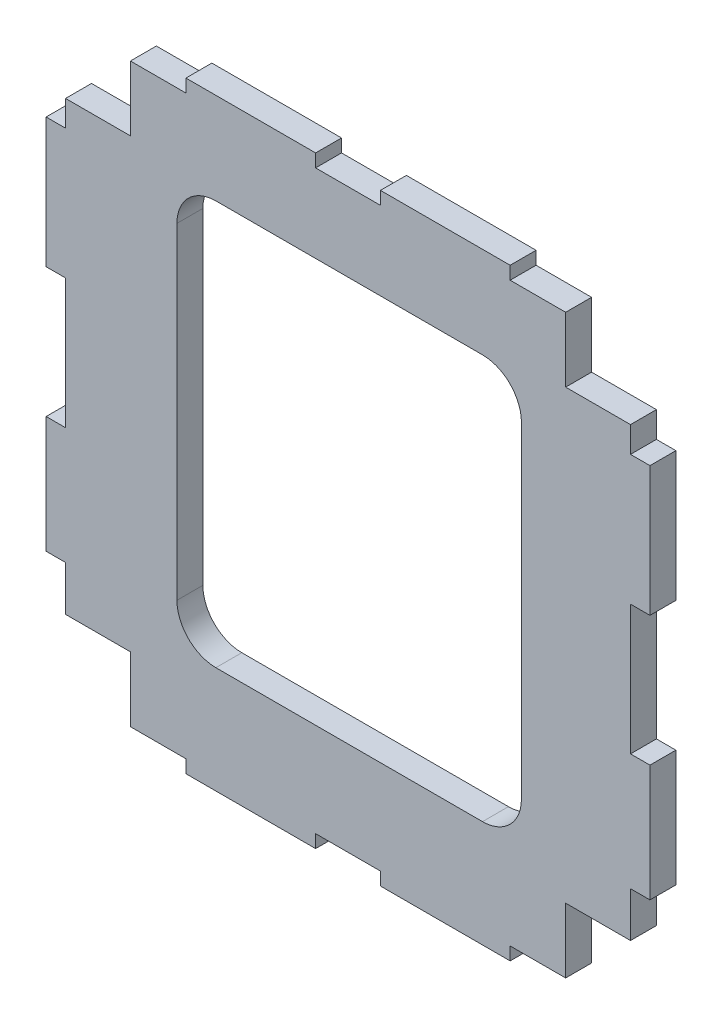
SolidWorks part; units mm, degrees
ref_plane "前视基准面" through (0, 0, 0) normal (0, 0, 1) x (1, 0, 0)
ref_plane "上视基准面" through (0, 0, 0) normal (0, 1, 0) x (1, 0, 0)
ref_plane "右视基准面" through (0, 0, 0) normal (1, 0, 0) x (0, 0, -1)
sketch "Model" plane through (0, 0, 0) normal (0, 0, 1) x (1, 0, 0)
  line L0 (58.8479, 46.6084) -> (38.2879, 46.6084)
  line L1 (61.8479, 43.6084) -> (61.8479, 18.4384)
  line L2 (38.2879, 15.4384) -> (58.8479, 15.4384)
  line L3 (35.2879, 43.6084) -> (35.2879, 18.4384)
  line L4 (31.6988, 52.6573) -> (35.9788, 52.6573)
  line L5 (35.9788, 52.6573) -> (35.9788, 53.6577)
  line L6 (35.9788, 53.6577) -> (45.9788, 53.6577)
  line L7 (45.9788, 53.6577) -> (45.9788, 52.6573)
  line L8 (45.9788, 52.6573) -> (50.9788, 52.6573)
  line L9 (50.9788, 52.6573) -> (50.9788, 53.6577)
  line L10 (50.9788, 53.6577) -> (60.9788, 53.6577)
  line L11 (60.9788, 53.6577) -> (60.9788, 52.6573)
  line L12 (60.9788, 52.6573) -> (65.2588, 52.6573)
  line L13 (31.6988, 8.2017) -> (35.9788, 8.2017)
  line L14 (35.9788, 8.2017) -> (35.9788, 7.2013)
  line L15 (35.9788, 7.2013) -> (45.9788, 7.2013)
  line L16 (45.9788, 7.2013) -> (45.9788, 8.2017)
  line L17 (45.9788, 8.2017) -> (50.9788, 8.2017)
  line L18 (50.9788, 8.2017) -> (50.9788, 7.2013)
  line L19 (50.9788, 7.2013) -> (60.9788, 7.2013)
  line L20 (60.9788, 7.2013) -> (60.9788, 8.2017)
  line L21 (60.9788, 8.2017) -> (65.2588, 8.2017)
  line L22 (26.6988, 47.6573) -> (31.6988, 47.6573)
  line L23 (31.6988, 47.6573) -> (31.6988, 52.6573)
  line L24 (26.6988, 13.2017) -> (31.6988, 13.2017)
  line L25 (31.6988, 13.2017) -> (31.6988, 8.2017)
  line L26 (26.6988, 47.6573) -> (26.6988, 45.6673)
  line L27 (26.6988, 45.6673) -> (25.1988, 45.6673)
  line L28 (25.1988, 35.6673) -> (26.6988, 35.6673)
  line L29 (26.6988, 35.6673) -> (26.6988, 25.6673)
  line L30 (26.6988, 25.6673) -> (25.1988, 25.6673)
  line L31 (25.1988, 16.6673) -> (26.6988, 16.6673)
  line L32 (26.6988, 16.6673) -> (26.6988, 15.5173)
  line L33 (26.6988, 15.5173) -> (26.6988, 13.2017)
  line L34 (25.1988, 45.6673) -> (25.1988, 35.6673)
  line L35 (25.1988, 25.6673) -> (25.1988, 16.6673)
  line L36 (70.2588, 47.6573) -> (65.2588, 47.6573)
  line L37 (65.2588, 47.6573) -> (65.2588, 52.6573)
  line L38 (70.2588, 13.2017) -> (65.2588, 13.2017)
  line L39 (65.2588, 13.2017) -> (65.2588, 8.2017)
  line L40 (70.2588, 47.6573) -> (70.2588, 45.6673)
  line L41 (70.2588, 45.6673) -> (71.7588, 45.6673)
  line L42 (71.7588, 35.6673) -> (70.2588, 35.6673)
  line L43 (70.2588, 35.6673) -> (70.2588, 25.6673)
  line L44 (70.2588, 25.6673) -> (71.7588, 25.6673)
  line L45 (71.7588, 16.6673) -> (70.2588, 16.6673)
  line L46 (70.2588, 16.6673) -> (70.2588, 15.5173)
  line L47 (70.2588, 15.5173) -> (70.2588, 13.2017)
  line L48 (71.7588, 45.6673) -> (71.7588, 35.6673)
  line L49 (71.7588, 25.6673) -> (71.7588, 16.6673)
  arc A0 (38.2879, 46.6084) -> (35.2879, 43.6084) centre (38.2879, 43.6084) ccw
  arc A1 (61.8479, 43.6084) -> (58.8479, 46.6084) centre (58.8479, 43.6084) ccw
  arc A2 (35.2879, 18.4384) -> (38.2879, 15.4384) centre (38.2879, 18.4384) ccw
  arc A3 (58.8479, 15.4384) -> (61.8479, 18.4384) centre (58.8479, 18.4384) ccw
extrude "凸台-拉伸1" add sketch "Model" along normal blind 2
